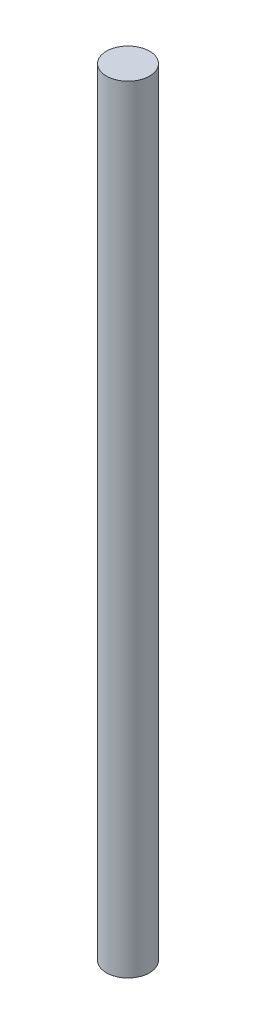
SolidWorks part; units mm, degrees
ref_plane "前视基准面" through (0, 0, 0) normal (0, 0, 1) x (1, 0, 0)
ref_plane "上视基准面" through (0, 0, 0) normal (0, 1, 0) x (1, 0, 0)
ref_plane "右视基准面" through (0, 0, 0) normal (1, 0, 0) x (0, 0, -1)
other "Configuration Table"
sketch "草图1" plane through (0, 0, 0) normal (0, 1, 0) x (1, 0, 0)
  circle A0 centre (0, 0) radius 3
extrude "凸台-拉伸1" add sketch "草图1" along normal blind 108
